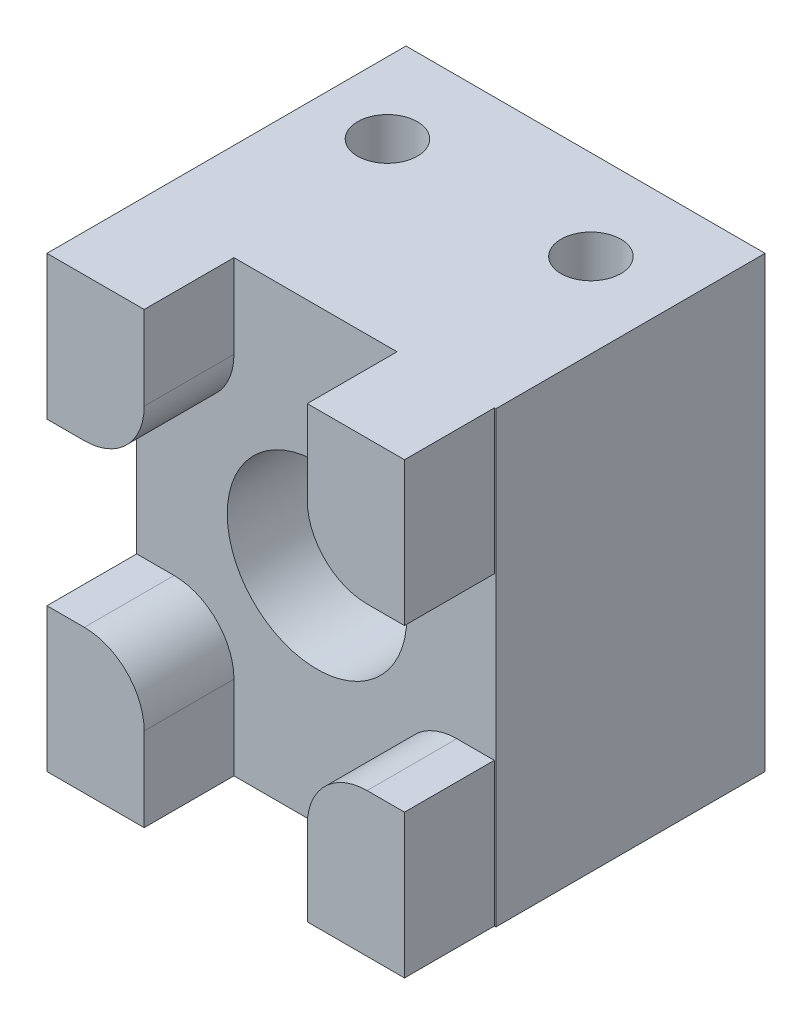
SolidWorks part; units mm, degrees
ref_plane "Front Plane" through (0, 0, 0) normal (0, 0, 1) x (1, 0, 0)
ref_plane "Top Plane" through (0, 0, 0) normal (0, 1, 0) x (1, 0, 0)
ref_plane "Right Plane" through (0, 0, 0) normal (1, 0, 0) x (0, 0, -1)
other "Graphic1"
ref_plane "Plane2" through (0, 0, 20) normal (0, 0, 1) x (1, 0, 0)
sketch "Sketch1" plane through (0, 0, 20) normal (0, 0, 1) x (1, 0, 0)
  line L1 (225, 440.5) -> (237, 440.5)
  line L2 (225, 440.5) -> (225, 425.5)
  line L3 (225, 425.5) -> (237, 425.5)
  line L4 (237, 440.5) -> (237, 425.5)
  dimension "D1" = 12
  dimension "D2" = 15
extrude "Boss-Extrude1" add sketch "Sketch1" along normal blind 9
sketch "Sketch2" plane through (0, 0, 29) normal (0, 0, 1) x (1, 0, 0)
  line L0 (233.7, 440.5) -> (233.7, 435.7)
  line L1 (225, 440.5) -> (228.25, 440.5)
  line L2 (225, 440.5) -> (225, 435.7)
  line L3 (225, 435.7) -> (228.25, 435.7)
  line L4 (228.25, 440.5) -> (228.25, 435.7)
  line L5 (233.7, 440.5) -> (236.95, 440.5)
  line L6 (236.95, 440.5) -> (236.95, 435.7)
  line L7 (233.7, 435.7) -> (236.95, 435.7)
  line L8 (233.7, 430.3) -> (233.7, 425.5)
  line L9 (233.7, 430.3) -> (236.95, 430.3)
  line L10 (236.95, 430.3) -> (236.95, 425.5)
  line L11 (233.7, 425.5) -> (236.95, 425.5)
  line L12 (225, 430.3) -> (225, 425.5)
  line L13 (225, 430.3) -> (228.25, 430.3)
  line L14 (228.25, 430.3) -> (228.25, 425.5)
  line L15 (225, 425.5) -> (228.25, 425.5)
  dimension "D1" = 3.25
  dimension "D2" = 4.8
  dimension "D3" = 2
  dimension "D4" = 2
extrude "Boss-Extrude2" add sketch "Sketch2" along normal blind 3
sketch "Sketch3" plane through (0, 0, 29) normal (0, 0, 1) x (1, 0, 0)
  circle A0 centre (231.0265, 432.9751) radius 3
  point P2 (231.0265, 432.9751)
extrude "Cut-Extrude1" cut sketch "Sketch3" against normal through all
fillet "Fillet1" radius 2 4 edges at (233.7, 430.3, 30.5) (228.25, 430.3, 30.5) (233.7, 435.7, 30.5) (228.25, 435.7, 30.5)
sketch "Sketch4" plane through (0, 425.5, 0) normal (0, -1, 0) x (-1, 0, 0)
  line L0 (-225, -20) -> (-237, -20) construction
  circle A0 centre (-227.3795, -23) radius 1
  circle A1 centre (-234.1795, -23) radius 1
  point P1 (0, 0)
  point P6 (-227.4039, -20)
  dimension "D1" = 3
extrude "Cut-Extrude2" cut sketch "Sketch4" against normal up to surface (15 mm away) up to face at (232.18, 440.5, 28.4)
